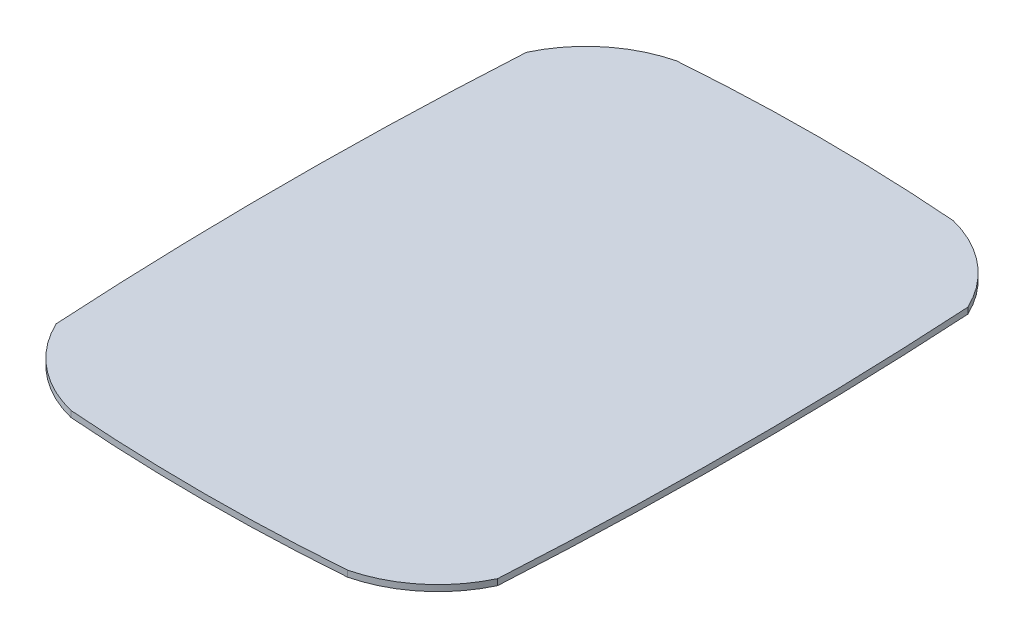
SolidWorks part; units mm, degrees
ref_plane "Front Plane" through (0, 0, 0) normal (0, 0, 1) x (1, 0, 0)
ref_plane "Top Plane" through (0, 0, 0) normal (0, 1, 0) x (1, 0, 0)
ref_plane "Right Plane" through (0, 0, 0) normal (1, 0, 0) x (0, 0, -1)
sketch "Sketch3" plane through (0, 0, 0) normal (0, 1, 0) x (1, 0, 0)
  arc A0 (-91.6492, -96.8338) -> (-91.6492, 98.3944) centre (1569.8143, 0.7803) cw
  arc A1 (-57.4696, -124.9376) -> (57.4696, -124.9376) centre (0, 622.082) ccw
  arc A2 (91.6492, -96.8338) -> (91.6492, 98.3944) centre (-1569.8143, 0.7803) ccw
  arc A3 (-57.4696, 126.4981) -> (57.4696, 126.4981) centre (0, -620.5215) cw
  arc A4 (-91.6492, -96.8338) -> (-57.4696, -124.9376) centre (-44.9936, -74.9279) ccw
  arc A5 (91.6492, -96.8338) -> (57.4696, -124.9376) centre (44.9936, -74.9279) cw
  arc A6 (91.6492, 98.3944) -> (57.4696, 126.4981) centre (44.9936, 76.4885) ccw
  arc A7 (-91.6492, 98.3944) -> (-57.4696, 126.4981) centre (-44.9936, 76.4885) cw
extrude "Boss-Extrude1" add sketch "Sketch3" along normal blind 2.54
sketch "Sketch4" plane through (0, 2.54, 0) normal (0, 1, 0) x (1, 0, 0)
  line L0 (-94.5143, 0.7803) -> (94.5143, 0.7803)
  line L1 (0, -127.1449) -> (0, 128.7055)
  line L2 (77.7288, 116.3008) -> (-77.7288, -114.7403)
  line L3 (-77.7288, 116.3008) -> (77.7288, -114.7403)
  line L4 (83.7325, 102.8322) -> (85.8067, 101.4366)
  line L5 (85.8067, 101.4366) -> (83.0154, 97.2882)
  line L9 (71.8504, 80.6947) -> (69.7762, 82.0904)
  line L10 (69.7762, 82.0904) -> (72.5675, 86.2387)
  line L11 (46.9602, 97.4423) -> (49.0344, 96.0466)
  line L12 (80.9412, 98.6838) -> (83.7325, 102.8322)
  line L13 (80.9412, 98.6838) -> (83.0154, 97.2882)
  line L14 (72.5675, 86.2387) -> (74.6417, 84.8431)
  line L15 (74.6417, 84.8431) -> (71.8504, 80.6947)
  line L16 (49.7515, 101.5906) -> (46.9602, 97.4423)
  line L17 (51.8257, 100.195) -> (49.7515, 101.5906)
  line L18 (49.0344, 96.0466) -> (51.8257, 100.195)
  line L19 (60.1994, 112.6401) -> (62.9907, 116.7884)
  line L20 (60.1994, 112.6401) -> (58.1253, 114.0357)
  line L21 (60.9165, 118.1841) -> (58.1253, 114.0357)
  line L22 (62.9907, 116.7884) -> (60.9165, 118.1841)
  point P5 (0, 0.7803)
sketch "Sketch6" plane through (0, 0, 0) normal (0, -1, 0) x (1, 0, 0)
  line L0 (77.7288, -116.3008) -> (-77.7288, 114.7403) construction
  line L1 (77.7288, -116.3008) -> (-77.7288, 114.7403)
  line L18 (-94.5143, -0.7803) -> (94.5143, -0.7803) construction
  line L19 (-77.7288, -116.3008) -> (77.7288, 114.7403) construction
  line L20 (0, 127.1449) -> (0, -128.7055) construction
  line L37 (-94.5143, -0.7803) -> (94.5143, -0.7803)
  line L38 (-77.7288, -116.3008) -> (77.7288, 114.7403)
  line L39 (0, 127.1449) -> (0, -128.7055)
  line L102 (84.7762, -10.7803) -> (89.7762, -10.7803)
  line L103 (84.7762, -13.2803) -> (84.7762, -10.7803)
  line L104 (89.7762, -13.2803) -> (84.7762, -13.2803)
  line L105 (89.7762, -10.7803) -> (89.7762, -13.2803)
  line L106 (69.7762, -10.7803) -> (69.7762, -13.2803)
  line L107 (64.7762, -10.7803) -> (69.7762, -10.7803)
  line L108 (64.7762, -13.2803) -> (64.7762, -10.7803)
  line L109 (69.7762, -13.2803) -> (64.7762, -13.2803)
  line L126 (84.7762, 11.7197) -> (84.7762, 9.2197)
  line L127 (89.7762, 11.7197) -> (84.7762, 11.7197)
  line L128 (89.7762, 9.2197) -> (89.7762, 11.7197)
  line L129 (84.7762, 9.2197) -> (89.7762, 9.2197)
  line L130 (64.7762, 9.2197) -> (69.7762, 9.2197)
  line L131 (64.7762, 11.7197) -> (64.7762, 9.2197)
  line L132 (69.7762, 11.7197) -> (64.7762, 11.7197)
  line L133 (69.7762, 9.2197) -> (69.7762, 11.7197)
  line L134 (-89.7762, 11.7197) -> (-84.7762, 11.7197)
  line L135 (-89.7762, 9.2197) -> (-89.7762, 11.7197)
  line L136 (-84.7762, 9.2197) -> (-89.7762, 9.2197)
  line L137 (-84.7762, 11.7197) -> (-84.7762, 9.2197)
  line L138 (-64.7762, 11.7197) -> (-64.7762, 9.2197)
  line L139 (-69.7762, 11.7197) -> (-64.7762, 11.7197)
  line L140 (-69.7762, 9.2197) -> (-69.7762, 11.7197)
  line L141 (-64.7762, 9.2197) -> (-69.7762, 9.2197)
  line L142 (-64.7762, -10.7803) -> (-69.7762, -10.7803)
  line L143 (-64.7762, -13.2803) -> (-64.7762, -10.7803)
  line L144 (-69.7762, -13.2803) -> (-64.7762, -13.2803)
  line L145 (-69.7762, -10.7803) -> (-69.7762, -13.2803)
  line L146 (-84.7762, -13.2803) -> (-84.7762, -10.7803)
  line L147 (-89.7762, -13.2803) -> (-84.7762, -13.2803)
  line L148 (-89.7762, -10.7803) -> (-89.7762, -13.2803)
  line L149 (-84.7762, -10.7803) -> (-89.7762, -10.7803)
  line L150 (83.6753, -102.8707) -> (81.6011, -104.2663)
  line L151 (65.1221, -115.3543) -> (62.3309, -111.2059)
  line L152 (62.3309, -111.2059) -> (60.2567, -112.6016)
  line L153 (60.2567, -112.6016) -> (63.0479, -116.7499)
  line L154 (63.0479, -116.7499) -> (65.1221, -115.3543)
  line L155 (51.8829, -100.1565) -> (53.9571, -98.7609)
  line L156 (53.9571, -98.7609) -> (51.1659, -94.6125)
  line L157 (51.1659, -94.6125) -> (49.0917, -96.0081)
  line L158 (49.0917, -96.0081) -> (51.8829, -100.1565)
  line L159 (80.884, -98.7223) -> (83.6753, -102.8707)
  line L160 (78.8098, -100.118) -> (80.884, -98.7223)
  line L161 (81.6011, -104.2663) -> (78.8098, -100.118)
  line L162 (69.719, -82.1289) -> (72.5102, -86.2773)
  line L163 (67.6448, -83.5245) -> (69.719, -82.1289)
  line L164 (70.4361, -87.6729) -> (67.6448, -83.5245)
  line L165 (72.5102, -86.2773) -> (70.4361, -87.6729)
  line L166 (-63.0479, -116.7499) -> (-65.1221, -115.3543)
  line L167 (-60.2567, -112.6016) -> (-63.0479, -116.7499)
  line L168 (-62.3309, -111.2059) -> (-60.2567, -112.6016)
  line L169 (-65.1221, -115.3543) -> (-62.3309, -111.2059)
  line L170 (-80.884, -98.7223) -> (-83.6753, -102.8707)
  line L171 (-78.8098, -100.118) -> (-80.884, -98.7223)
  line L172 (-81.6011, -104.2663) -> (-78.8098, -100.118)
  line L173 (-83.6753, -102.8707) -> (-81.6011, -104.2663)
  line L174 (-67.6448, -83.5245) -> (-69.719, -82.1289)
  line L175 (-70.4361, -87.6729) -> (-67.6448, -83.5245)
  line L176 (-72.5102, -86.2773) -> (-70.4361, -87.6729)
  line L177 (-69.719, -82.1289) -> (-72.5102, -86.2773)
  line L178 (-49.0917, -96.0081) -> (-51.8829, -100.1565)
  line L179 (-51.1659, -94.6125) -> (-49.0917, -96.0081)
  line L180 (-53.9571, -98.7609) -> (-51.1659, -94.6125)
  line L181 (-51.8829, -100.1565) -> (-53.9571, -98.7609)
  line L182 (-70.4361, 86.1123) -> (-67.6448, 81.964)
  line L183 (-72.5102, 84.7167) -> (-70.4361, 86.1123)
  line L184 (-69.719, 80.5683) -> (-72.5102, 84.7167)
  line L185 (-67.6448, 81.964) -> (-69.719, 80.5683)
  line L186 (-78.8098, 98.5574) -> (-80.884, 97.1618)
  line L187 (-81.6011, 102.7058) -> (-78.8098, 98.5574)
  line L188 (-83.6753, 101.3101) -> (-81.6011, 102.7058)
  line L189 (-80.884, 97.1618) -> (-83.6753, 101.3101)
  line L190 (-51.1659, 93.0519) -> (-49.0917, 94.4476)
  line L191 (-53.9571, 97.2003) -> (-51.1659, 93.0519)
  line L192 (-51.8829, 98.5959) -> (-53.9571, 97.2003)
  line L193 (-49.0917, 94.4476) -> (-51.8829, 98.5959)
  line L194 (-60.2567, 111.041) -> (-63.0479, 115.1894)
  line L195 (-62.3309, 109.6454) -> (-60.2567, 111.041)
  line L196 (-65.1221, 113.7937) -> (-62.3309, 109.6454)
  line L197 (-63.0479, 115.1894) -> (-65.1221, 113.7937)
  line L198 (63.0479, 115.1894) -> (65.1221, 113.7937)
  line L199 (60.2567, 111.041) -> (63.0479, 115.1894)
  line L200 (62.3309, 109.6454) -> (60.2567, 111.041)
  line L201 (65.1221, 113.7937) -> (62.3309, 109.6454)
  line L202 (80.884, 97.1618) -> (83.6753, 101.3101)
  line L203 (78.8098, 98.5574) -> (80.884, 97.1618)
  line L204 (81.6011, 102.7058) -> (78.8098, 98.5574)
  line L205 (83.6753, 101.3101) -> (81.6011, 102.7058)
  line L206 (67.6448, 81.964) -> (69.719, 80.5683)
  line L207 (70.4361, 86.1123) -> (67.6448, 81.964)
  line L208 (72.5102, 84.7167) -> (70.4361, 86.1123)
  line L209 (69.719, 80.5683) -> (72.5102, 84.7167)
  line L210 (49.0917, 94.4476) -> (51.8829, 98.5959)
  line L211 (51.1659, 93.0519) -> (49.0917, 94.4476)
  line L212 (53.9571, 97.2003) -> (51.1659, 93.0519)
  line L213 (51.8829, 98.5959) -> (53.9571, 97.2003)
  arc A8 (-57.4696, 124.9376) -> (-91.6492, 96.8338) centre (-44.9936, 74.9279) ccw
  arc A9 (-91.6492, 96.8338) -> (-91.6492, -98.3944) centre (1569.8143, -0.7803) ccw
  arc A10 (-91.6492, -98.3944) -> (-57.4696, -126.4981) centre (-44.9936, -76.4885) ccw
  arc A11 (-57.4696, -126.4981) -> (57.4696, -126.4981) centre (0, 620.5215) ccw
  arc A12 (57.4696, -126.4981) -> (91.6492, -98.3944) centre (44.9936, -76.4885) ccw
  arc A13 (91.6492, -98.3944) -> (91.6492, 96.8338) centre (-1569.8143, -0.7803) ccw
  arc A14 (91.6492, 96.8338) -> (57.4696, 124.9376) centre (44.9936, 74.9279) ccw
  arc A15 (57.4696, 124.9376) -> (-57.4696, 124.9376) centre (0, -622.082) ccw
  arc A16 (-57.4696, 124.9376) -> (-91.6492, 96.8338) centre (-44.9936, 74.9279) ccw
  arc A17 (-91.6492, 96.8338) -> (-91.6492, -98.3944) centre (1569.8143, -0.7803) ccw
  arc A18 (-91.6492, -98.3944) -> (-57.4696, -126.4981) centre (-44.9936, -76.4885) ccw
  arc A19 (-57.4696, -126.4981) -> (57.4696, -126.4981) centre (0, 620.5215) ccw
  arc A20 (57.4696, -126.4981) -> (91.6492, -98.3944) centre (44.9936, -76.4885) ccw
  arc A21 (91.6492, -98.3944) -> (91.6492, 96.8338) centre (-1569.8143, -0.7803) ccw
  arc A22 (91.6492, 96.8338) -> (57.4696, 124.9376) centre (44.9936, 74.9279) ccw
  arc A23 (57.4696, 124.9376) -> (-57.4696, 124.9376) centre (0, -622.082) ccw
  dimension "D2" = 10
  dimension "D3" = 10
  dimension "D1" = 0
extrude "Cut-Extrude2" cut sketch "Sketch6" against normal blind 0.2 contours L189 L186 L187 L188 | L194 L197 L196 L195 | L185 L182 L183 L184 | L190 L193 L192 L191 | L213 L210 L211 L212 | L201 L198 L199 L200 | L206 L209 L208 L207 | L202 L205 L204 L203 | L130 L133 L132 L131 | L126 L129 L128 L127 | L109 L106 L107 L108 | L105 L102 L103 L104 | L165 L162 L163 L164 | L161 L150 L159 L160 | L153 L154 L151 L152 | L157 L158 L155 L156 | L169 L166 L167 L168 | L181 L178 L179 L180 | L170 L173 L172 L171 | L174 L177 L176 L175 | L141 L138 L139 L140 | L142 L145 L144 L143 | L146 L149 L148 L147 | L137 L134 L135 L136
